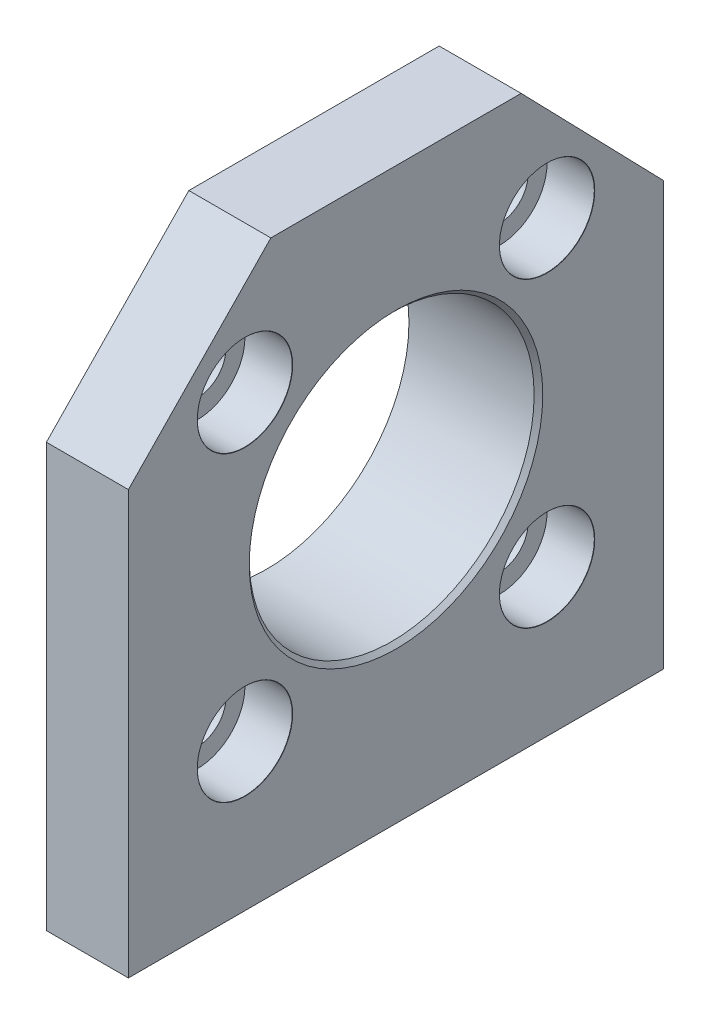
SolidWorks part; units mm, degrees
ref_plane "Plano frontal" through (0, 0, 0) normal (0, 0, 1) x (1, 0, 0)
ref_plane "Plano superior" through (0, 0, 0) normal (0, 1, 0) x (1, 0, 0)
ref_plane "Plano direito" through (0, 0, 0) normal (1, 0, 0) x (0, 0, -1)
sketch "Esboço1" plane through (0, 0, 0) normal (1, 0, 0) x (0, 0, -1)
  line L0 (0, 49) -> (16.5, 66)
  line L1 (0, 0) -> (62, 0)
  line L2 (0, 0) -> (0, 49)
  line L3 (0, 49) -> (62, 49)
  line L4 (62, 0) -> (62, 49)
  line L5 (16.5, 66) -> (45.5, 66)
  line L6 (45.5, 66) -> (62, 49)
  line L7 (31, 0) -> (31, 66) construction
  point P5 (31, 66)
  dimension "D1" = 66
  dimension "D2" = 49
  dimension "D3" = 62
  dimension "D4" = 29
extrude "Ressalto-extrusão1" add sketch "Esboço1" against normal blind 9.5 contours L3 L7 L5 L0 | L7 L3 L6 L5 | L1 L7 L3 L2 | L7 L1 L4 L3
hole_wizard "Rebaixo para parafuso com cabeça redonda de M61" positions "Esboço3" profile "Esboço4" counterbore size "M6" standard "ISO" end condition through all
sketch "Esboço3" plane through (0, 0, 0) normal (1, 0, 0) x (0, 0, -1)
  line L0 (0, 0) -> (62, 0) construction
  line L1 (16.5, 66) -> (45.5, 66) construction
  point P0 (13.5, 52)
  point P2 (48.5, 52)
  point P4 (48.5, 17)
  point P6 (13.5, 17)
  point P9 (0, 0)
  point P10 (0, 0)
  point P11 (0, 0)
  point P12 (0, 0)
  point P17 (31, 66)
  dimension "D1" = 35
  dimension "D2" = 35
  dimension "D3" = 17
  dimension "D4" = 17.5
sketch "Esboço4" plane through (0, 52, -13.5) normal (0, 1, 0) x (0, 0, -1)
  line L0 (0, 0) -> (0, 9.5)
  line L1 (0, 9.5) -> (3.3, 9.5)
  line L3 (3.3, 9.5) -> (3.3, 5.5)
  line L4 (5.5, 5.5) -> (3.3, 5.5)
  line L5 (5.5, 5.5) -> (5.5, 0.025)
  line L6 (5.5, 0.025) -> (5.525, 0)
  line L7 (5.525, 0) -> (0, 0)
  line L8 (-5.5, 0.025) -> (-5.525, 0) construction
  line L11 (0, -6.35) -> (0, 107.95) construction
  dimension "Thru Hole Dia." = 6.6
  dimension "Thru Hole Depth" = 9.5
  dimension "C'Bore Dia." = 11
  dimension "C'Bore Depth" = 5.5
  dimension "Near C'Sink Dia." = 11.05
  dimension "Near C'Sink Angle" = 90
sketch "Esboço8" plane through (-9.5, 0, 0) normal (-1, 0, 0) x (0, 0, 1)
  circle A0 centre (-31, 34.5) radius 19.9
  circle A1 centre (-13.5, 52) radius 3.3 construction
  circle A2 centre (-48.5, 17) radius 3.3 construction
  dimension "D1" = 39.8
  dimension "D3" = 17.5
  dimension "D2" = 17.5
extrude "Ressalto-extrusão2" add sketch "Esboço8" along normal blind 5.5
sketch "Esboço5" plane through (0, 0, 0) normal (1, 0, 0) x (0, 0, -1)
  circle A0 centre (31, 34.5) radius 16.5
  circle A1 centre (13.5, 52) radius 3.3 construction
  circle A2 centre (13.5, 17) radius 5.5 construction
  dimension "D1" = 33
  dimension "D2" = 17.5
  dimension "D3" = 17.5
extrude "Corte-extrusão1" cut sketch "Esboço5" against normal through all
chamfer "Chanfro1" distance 0.5 angle 45 1 edges at (0, 34.5, -47.5)
